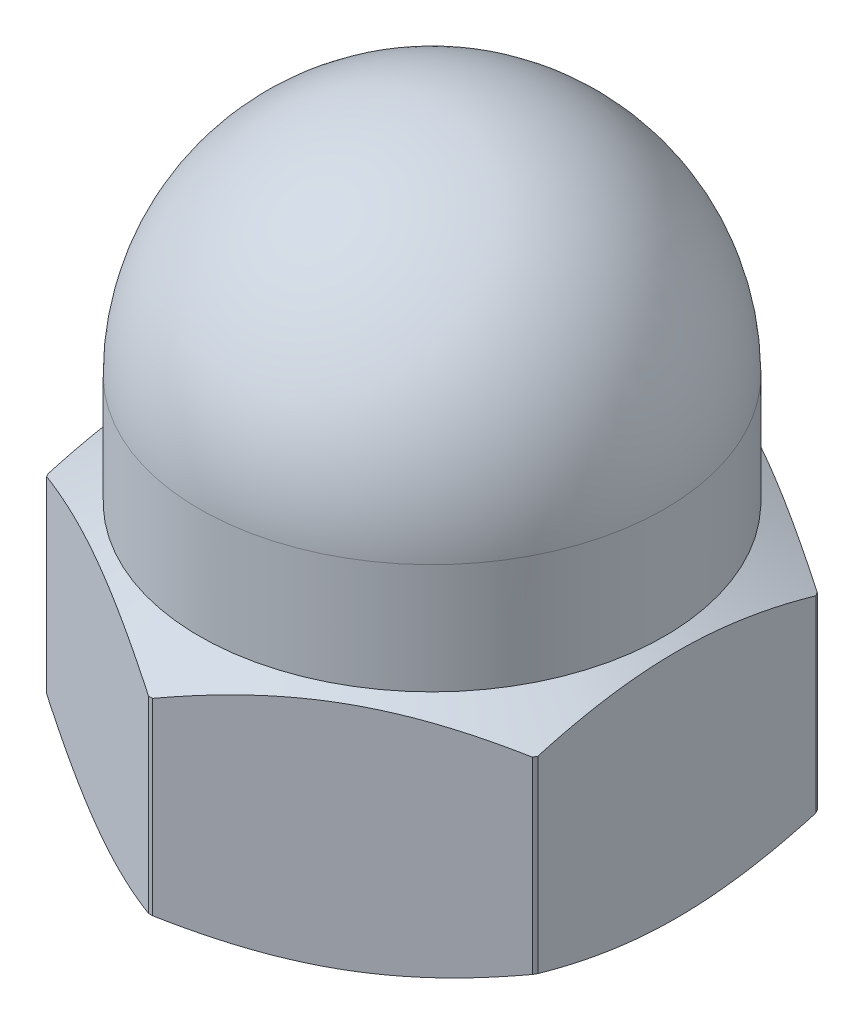
SolidWorks part; units mm, degrees
ref_plane "Плоскость1" through (0, 0, 0) normal (0, 0, 1) x (1, 0, 0)
ref_plane "Плоскость2" through (0, 0, 0) normal (0, 1, 0) x (1, 0, 0)
ref_plane "Плоскость3" through (0, 0, 0) normal (1, 0, 0) x (0, 0, -1)
sketch "Эскиз1" plane through (0, 0, 0) normal (0, 0, 1) x (1, 0, 0)
  line L0 (4.75, 5) -> (8.7489, 5) construction
  line L1 (5.75, 0.5774) -> (5.75, 4.4226)
  line L2 (2.6, 0) -> (4.75, 0)
  line L3 (4.75, 7.25) -> (4.75, 5)
  line L4 (0, 18.3723) -> (0, -29.5449) construction
  line L5 (0, 12) -> (0, 10)
  line L6 (2.6, 8) -> (2.6, 0)
  line L7 (2.6, 8) -> (0, 10)
  line L8 (4.75, 5) -> (5.75, 4.4226)
  line L9 (4.75, 0) -> (5.75, 0.5774)
  arc A0 (4.75, 7.25) -> (0, 12) centre (0, 7.25) ccw
  dimension "D2" = 11.5
  dimension "D3" = 12
  dimension "D4" = 1
  dimension "D5" = 8
  dimension "D7" = 5.2
  dimension "D8" = 30
  dimension "D9" = 5
  dimension "D10" = 30
  dimension "D11" = 9.5
  dimension "D12" = 2
revolve "Основание-Повернуть" add sketch "Эскиз1" angle 360 about L4
sketch "Эскиз2" plane through (0, 0, 0) normal (0, 1, 0) x (1, 0, 0)
  line L1 (0, 5.7735) -> (-5, 2.8868)
  line L2 (-5, 2.8868) -> (-5, -2.8868)
  line L3 (-5, -2.8868) -> (0, -5.7735)
  line L4 (0, -5.7735) -> (5, -2.8868)
  line L5 (5, -2.8868) -> (5, 2.8868)
  line L6 (5, 2.8868) -> (0, 5.7735)
  circle A0 centre (0, 0) radius 5 construction
  dimension "D1" = 10
  dimension "D2" = 11.547
extrude "Вырез-Вытянуть1" cut sketch "Эскиз2" along normal through all flip side to cut
chamfer "Фаска1" distance 0.6 angle 45 1 edges at (-2.6, 0, 0)
fillet "Скругление1" [suppressed] radius 0.3
